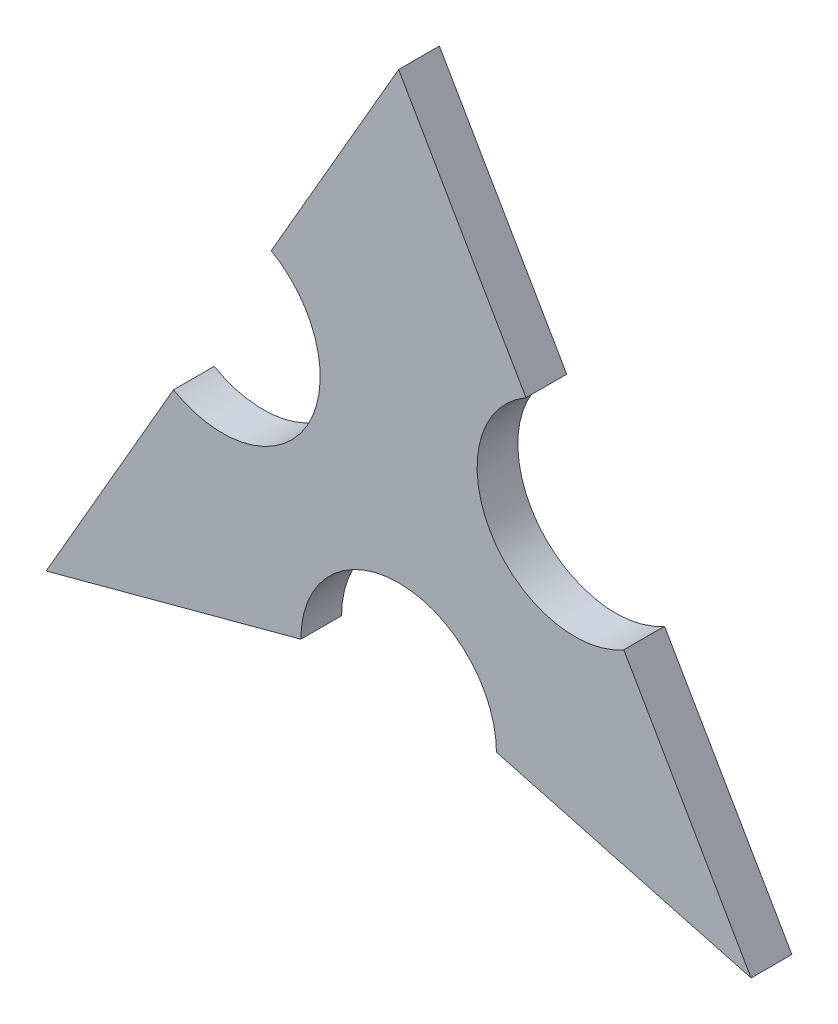
SolidWorks part; units mm, degrees
ref_plane "Front Plane" through (0, 0, 0) normal (0, 0, 1) x (1, 0, 0)
ref_plane "Top Plane" through (0, 0, 0) normal (0, 1, 0) x (1, 0, 0)
ref_plane "Right Plane" through (0, 0, 0) normal (1, 0, 0) x (0, 0, -1)
sketch "Sketch1" plane through (0, 0, 0) normal (0, 0, 1) x (1, 0, 0)
  line L0 (0, 149.8224) -> (-31.25, 95.6958)
  line L1 (0, 149.8224) -> (31.25, 95.6958)
  line L2 (-86.5, 0) -> (86.5, 0) construction
  line L3 (-55.25, 54.1266) -> (-86.5, 0)
  line L4 (-86.5, 0) -> (-24, 16.7468)
  line L5 (0, -68.411) -> (0, 173.7183) construction
  line L7 (55.25, 54.1266) -> (86.5, 0)
  line L8 (86.5, 0) -> (24, 16.7468)
  arc A0 (-55.25, 54.1266) -> (-31.25, 95.6958) centre (-43.25, 74.9112) ccw
  arc A2 (55.25, 54.1266) -> (31.25, 95.6958) centre (43.25, 74.9112) cw
  arc A3 (24, 16.7468) -> (-24, 16.7468) centre (0, 16.7468) ccw
  point P2 (0, 0)
  point P16 (0, 0)
  dimension "D5" = 48
  dimension "D3" = 48
  dimension "D1" = 60
  dimension "D2" = 173
  dimension "D4" = 45
  dimension "D6" = 86.5
  dimension "D7" = 45
extrude "Boss-Extrude1" add sketch "Sketch1" along normal mid plane 10
